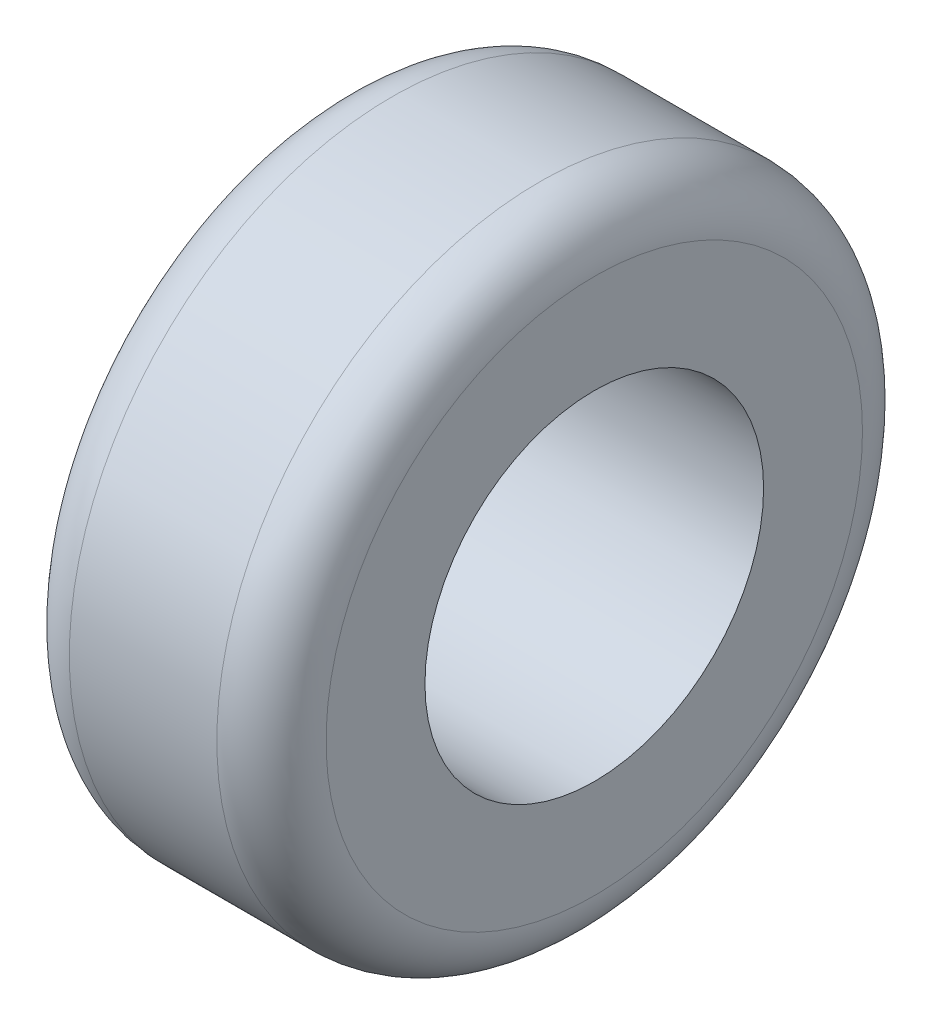
SolidWorks part; units mm, degrees
ref_plane "Plan de face" through (0, 0, 0) normal (0, 0, 1) x (1, 0, 0)
ref_plane "Plan de dessus" through (0, 0, 0) normal (0, 1, 0) x (1, 0, 0)
ref_plane "Plan de droite" through (0, 0, 0) normal (1, 0, 0) x (0, 0, -1)
sketch "Esquisse1" plane through (0, 0, 0) normal (1, 0, 0) x (0, 0, -1)
  circle A0 centre (0, 0) radius 11.82
  dimension "D1" = 23.64
extrude "Boss.-Extru.1" add sketch "Esquisse1" along normal blind 9.4
sketch "Esquisse2" plane through (9.4, 0, 0) normal (1, 0, 0) x (0, 0, -1)
  circle A0 centre (0, 0) radius 6.2
  dimension "D1" = 12.4
extrude "Enlèv. mat.-Extru.1" cut sketch "Esquisse2" against normal through all
fillet "Congé3" radius 2 2 edges at (9.4, 0, -11.82) (0, 0, -11.82)
